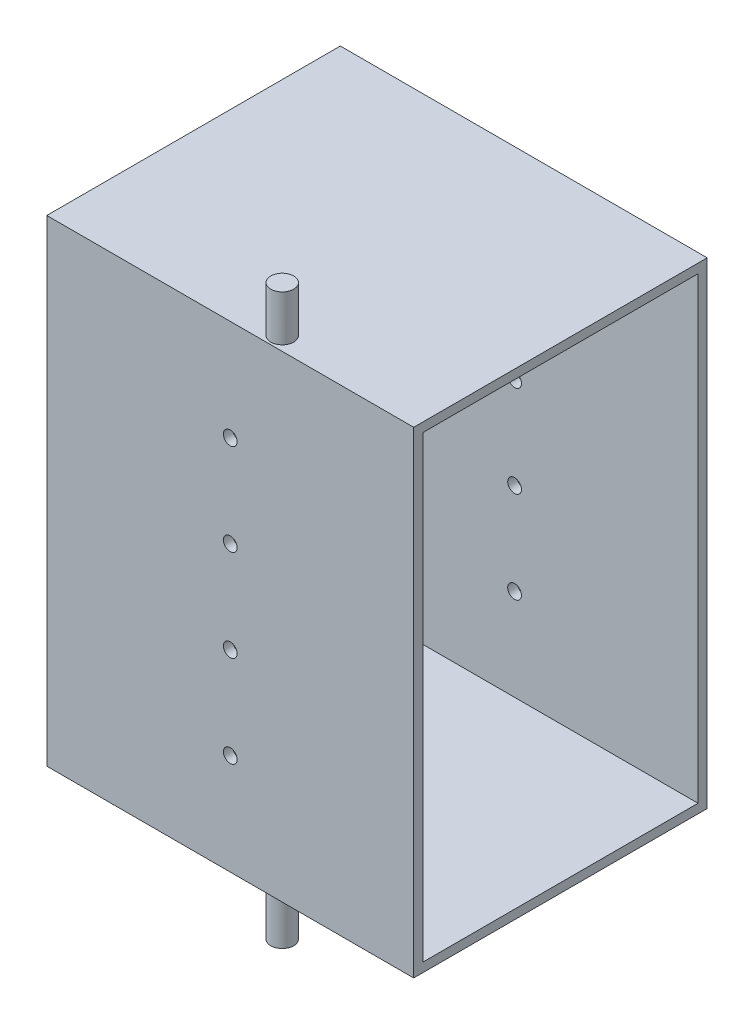
SolidWorks part; units mm, degrees
ref_plane "Front Plane" through (0, 0, 0) normal (0, 0, 1) x (1, 0, 0)
ref_plane "Top Plane" through (0, 0, 0) normal (0, 1, 0) x (1, 0, 0)
ref_plane "Right Plane" through (0, 0, 0) normal (1, 0, 0) x (0, 0, -1)
other "Configuration Table"
sketch "Sketch1" plane through (0, 0, 0) normal (1, 0, 0) x (0, 0, -1)
  line L1 (30, 90) -> (-30, 90)
  line L2 (30, 90) -> (30, 190)
  line L3 (30, 190) -> (-30, 190)
  line L4 (-30, 90) -> (-30, 190)
  line L5 (30, 90) -> (-30, 190) construction
  line L6 (30, 190) -> (-30, 90) construction
extrude "Duct_Throat" add sketch "Sketch1" along normal blind 80 from offset 18
shell "Carbon_Wall_Shell" thickness 2
sketch "Sketch2" plane through (0, 0, 0) normal (0, 0, 1) x (1, 0, 0)
  circle A0 centre (58, 110) radius 1.5
  circle A1 centre (58, 130) radius 1.5
  circle A2 centre (58, 150) radius 1.5
  circle A3 centre (58, 170) radius 1.5
extrude "Pivot_Hole_Pairs" cut sketch "Sketch2" against normal through all and the other way through all
sketch "Sketch3" plane through (0, 192, 0) normal (0, 1, 0) x (1, 0, 0)
  circle A0 centre (66.3423, -29) radius 2.5
extrude "SMA_Anchor_Peg" add sketch "Sketch3" along normal blind 10
sketch "Sketch4" plane through (0, 88, 0) normal (0, -1, 0) x (1, 0, 0)
  circle A0 centre (66.3423, 29) radius 2.5
extrude "Bias_Anchor_Peg" add sketch "Sketch4" along normal blind 10
